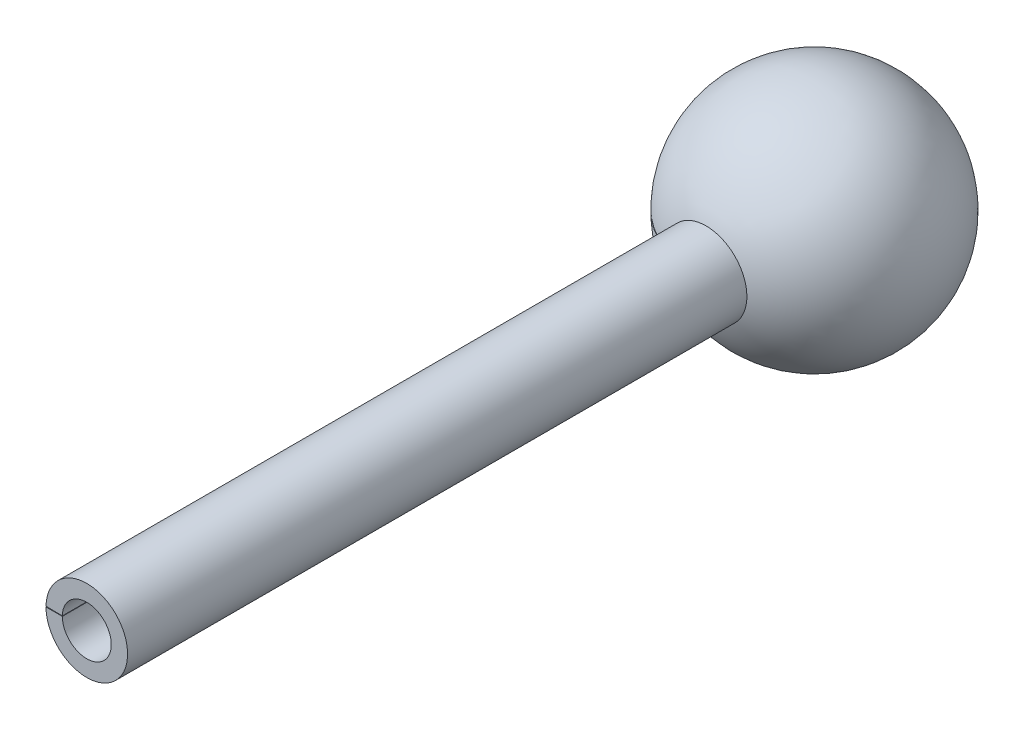
SolidWorks part; units mm, degrees
ref_plane "Front Plane" through (0, 0, 0) normal (0, 0, 1) x (1, 0, 0)
ref_plane "Top Plane" through (0, 0, 0) normal (0, 1, 0) x (1, 0, 0)
ref_plane "Right Plane" through (0, 0, 0) normal (1, 0, 0) x (0, 0, -1)
sketch "Sketch2" plane through (0, 0, 0) normal (0, 1, 0) x (1, 0, 0)
  line L0 (0, 28.3771) -> (0, -28.3771)
  line L1 (0, -28.3771) -> (0, -178.3771)
  line L2 (0, -178.3771) -> (-10, -178.3771)
  line L3 (-10, -178.3771) -> (-10, -26.5568)
  arc A0 (0, 28.3771) -> (0, -28.3771) centre (0, 0) ccw
  dimension "D1" = 10
  dimension "D4" = 28.3771
  dimension "D3" = 150
revolve "Revolve4" add sketch "Sketch2" angle 359 about L1
sketch "Sketch9" plane through (0, 0, 178.3771) normal (0, 0, 1) x (1, 0, 0)
  circle A0 centre (0, 0) radius 6
  dimension "D1" = 12
extrude "Cut-Extrude2" cut sketch "Sketch9" against normal blind 113
